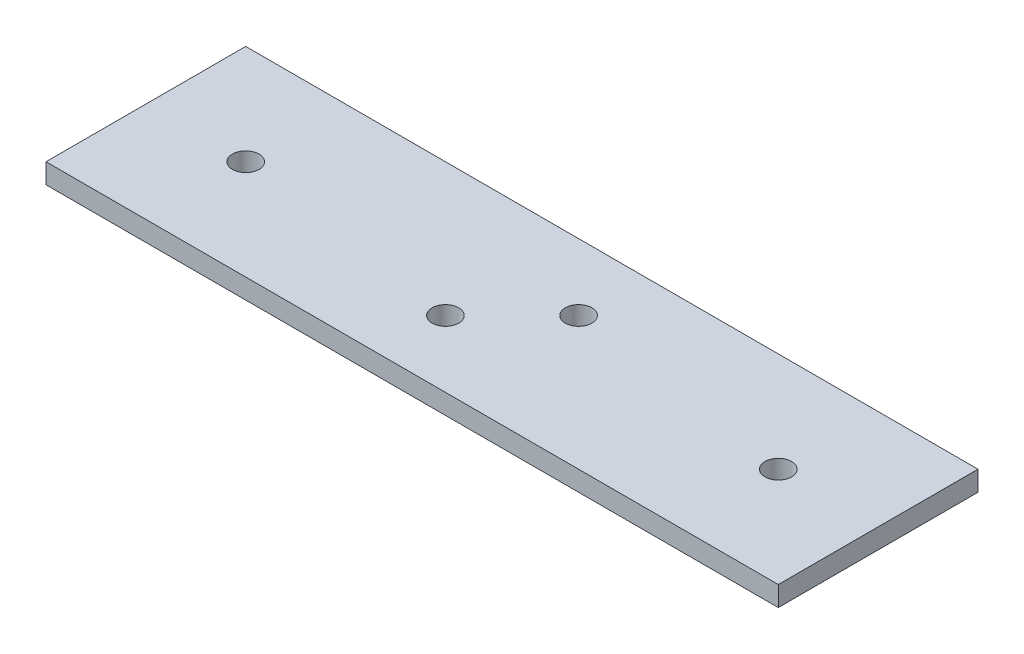
SolidWorks part; units mm, degrees
ref_plane "Front Plane" through (0, 0, 0) normal (0, 0, 1) x (1, 0, 0)
ref_plane "Top Plane" through (0, 0, 0) normal (0, 1, 0) x (1, 0, 0)
ref_plane "Right Plane" through (0, 0, 0) normal (1, 0, 0) x (0, 0, -1)
sketch "Sketch1" plane through (0, 0, 0) normal (0, 1, 0) x (1, 0, 0)
  line L0 (0, 0) -> (0, -23.3916) construction
  line L1 (55, -15) -> (-55, -15)
  line L2 (55, -15) -> (55, 15)
  line L3 (55, 15) -> (-55, 15)
  line L4 (-55, -15) -> (-55, 15)
  line L5 (55, -15) -> (-55, 15) construction
  line L6 (55, 15) -> (-55, -15) construction
  circle A0 centre (5, 5) radius 2
  circle A1 centre (-5, -5) radius 2
  circle A2 centre (-40, 0) radius 2
  circle A3 centre (40, 0) radius 2
  point P0 (0, 0)
  point P14 (-55, 0)
  point P17 (0, 0)
  dimension "D3" = 4
  dimension "D4" = 4
  dimension "D7" = 4
  dimension "D1" = 30
  dimension "D2" = 110
  dimension "D5" = 5
  dimension "D6" = 5
  dimension "D8" = 15
  dimension "D9" = 15
  dimension "D10" = 10
  dimension "D11" = 10
extrude "Boss-Extrude1" add sketch "Sketch1" along normal blind 3
